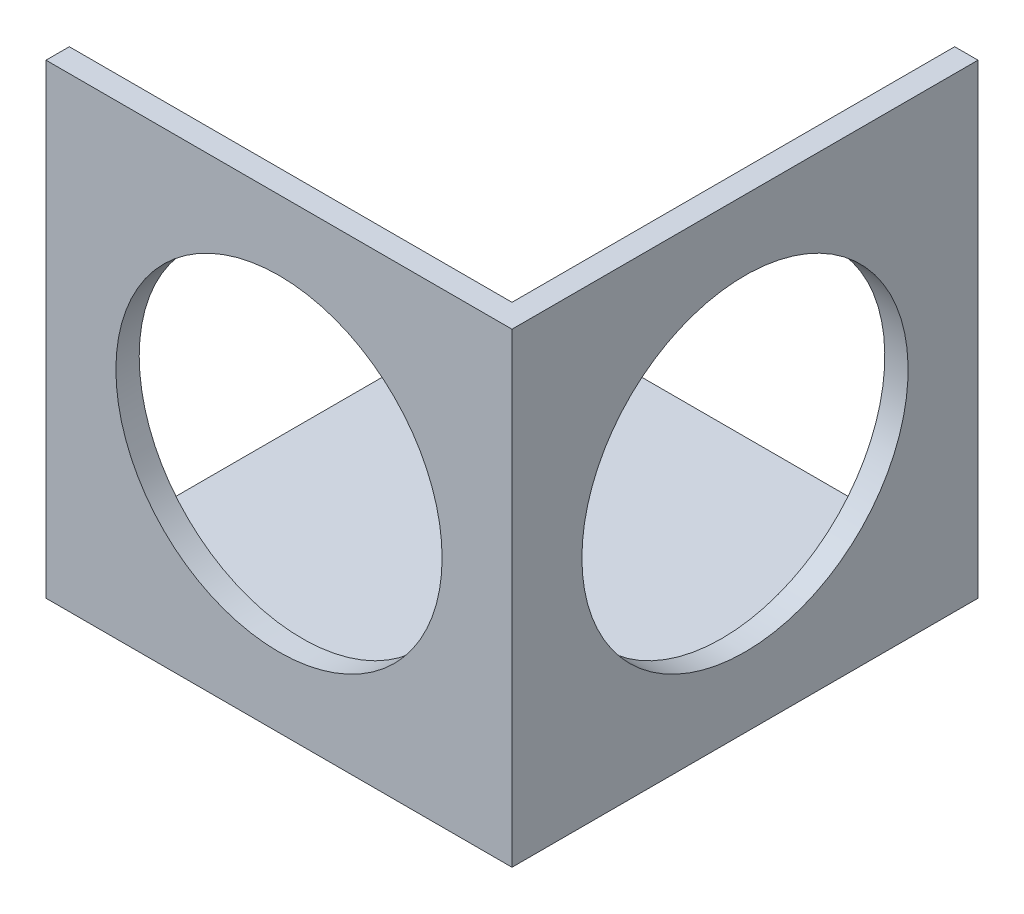
SolidWorks part; units mm, degrees
ref_plane "Plan de face" through (0, 0, 0) normal (0, 0, 1) x (1, 0, 0)
ref_plane "Plan de dessus" through (0, 0, 0) normal (0, 1, 0) x (1, 0, 0)
ref_plane "Plan de droite" through (0, 0, 0) normal (1, 0, 0) x (0, 0, -1)
sketch "Esquisse4" plane through (0, 0, 0) normal (0, 0, 1) x (1, 0, 0)
  line L1 (-48.4358, 46.1981) -> (51.5642, 46.1981)
  line L2 (-48.4358, 46.1981) -> (-48.4358, -53.8019)
  line L3 (-48.4358, -53.8019) -> (51.5642, -53.8019)
  line L4 (51.5642, 46.1981) -> (51.5642, -53.8019)
  line L5 (-43.4358, 41.1981) -> (46.5642, 41.1981)
  line L6 (-43.4358, 41.1981) -> (-43.4358, -48.8019)
  line L7 (-43.4358, -48.8019) -> (46.5642, -48.8019)
  line L8 (46.5642, 41.1981) -> (46.5642, -48.8019)
  dimension "D1" = 100
  dimension "D2" = 100
  dimension "D3" = 90
  dimension "D4" = 90
  dimension "D5" = 5
  dimension "D6" = 5
extrude "Boss.-Extru.1" add sketch "Esquisse4" along normal blind 100
sketch "Esquisse5" plane through (0, 0, 100) normal (0, 0, 1) x (1, 0, 0)
  line L0 (51.5642, 46.1981) -> (-48.4358, 46.1981) construction
  line L1 (-48.4358, 46.1981) -> (51.5642, 46.1981)
  line L2 (-48.4358, 46.1981) -> (-48.4358, -53.8019)
  line L3 (-48.4358, -53.8019) -> (51.5642, -53.8019)
  line L4 (51.5642, 46.1981) -> (51.5642, -53.8019)
  line L5 (-48.4358, 46.1981) -> (-48.4358, -53.8019) construction
extrude "Boss.-Extru.2" add sketch "Esquisse5" against normal blind 10
sketch "Esquisse6" plane through (0, 0, 0) normal (0, 0, -1) x (-1, 0, 0)
  line L0 (-51.5642, 46.1981) -> (48.4358, 46.1981) construction
  line L1 (-46.5642, 46.1981) -> (48.4358, 46.1981)
  line L2 (-46.5642, 46.1981) -> (-46.5642, -48.8017)
  line L3 (-46.5642, -48.8017) -> (48.4358, -48.8017)
  line L4 (48.4358, 46.1981) -> (48.4358, -48.8017)
  line L5 (48.4358, 46.1981) -> (48.4358, -53.8019) construction
extrude "Enlèv. mat.-Extru.1" cut sketch "Esquisse6" against normal blind 95
sketch "Esquisse7" plane through (0, -48.8017, 0) normal (0, 1, 0) x (1, 0, 0)
  line L1 (46.5642, -95) -> (-48.4358, -95)
  line L2 (46.5642, -95) -> (46.5642, 0)
  line L3 (46.5642, 0) -> (-48.4358, 0)
  line L4 (-48.4358, -95) -> (-48.4358, 0)
extrude "Enlèv. mat.-Extru.2" cut sketch "Esquisse7" against normal blind 1
sketch "Esquisse8" plane through (0, -49.8017, 0) normal (0, 1, 0) x (1, 0, 0)
  line L1 (46.5642, -95) -> (-48.4358, -95)
  line L2 (46.5642, -95) -> (46.5642, 0)
  line L3 (46.5642, 0) -> (-48.4358, 0)
  line L4 (-48.4358, -95) -> (-48.4358, 0)
extrude "Boss.-Extru.3" add sketch "Esquisse8" along normal blind 1
sketch "Esquisse9" plane through (0, 0, 95) normal (0, 0, -1) x (-1, 0, 0)
  line L0 (48.4358, -48.8017) -> (48.4358, 46.1981) construction
  line L1 (-46.5642, -48.8017) -> (43.4358, -48.8017)
  line L2 (-46.5642, -48.8017) -> (-46.5642, 41.1981)
  line L3 (-46.5642, 41.1981) -> (43.4358, 41.1981)
  line L4 (43.4358, -48.8017) -> (43.4358, 41.1981)
  line L5 (48.4358, 46.1981) -> (-46.5642, 46.1981) construction
  line L6 (43.4358, 41.1981) -> (-46.5642, -48.8017)
  circle A0 centre (-1.5642, -3.8018) radius 35
  dimension "D1" = 5
  dimension "D2" = 5
extrude "Enlèv. mat.-Extru.4" cut sketch "Esquisse9" against normal blind 55.5 contours L6 A0 | L6 A0
sketch "Esquisse11" plane through (46.5642, 0, 0) normal (-1, 0, 0) x (0, 0, 1)
  line L0 (0, -48.8017) -> (0, 46.1981) construction
  line L1 (95, -48.8017) -> (5, -48.8017)
  line L2 (95, -48.8017) -> (95, 41.1981)
  line L3 (95, 41.1981) -> (5, 41.1981)
  line L4 (5, -48.8017) -> (5, 41.1981)
  line L5 (95, 46.1981) -> (0, 46.1981) construction
  line L6 (5, 41.1981) -> (95, -48.8017)
  circle A0 centre (50, -3.8018) radius 35
  dimension "D1" = 5
  dimension "D2" = 5
extrude "Enlèv. mat.-Extru.5" cut sketch "Esquisse11" against normal blind 21.5 contours L6 A0 | L6 A0
